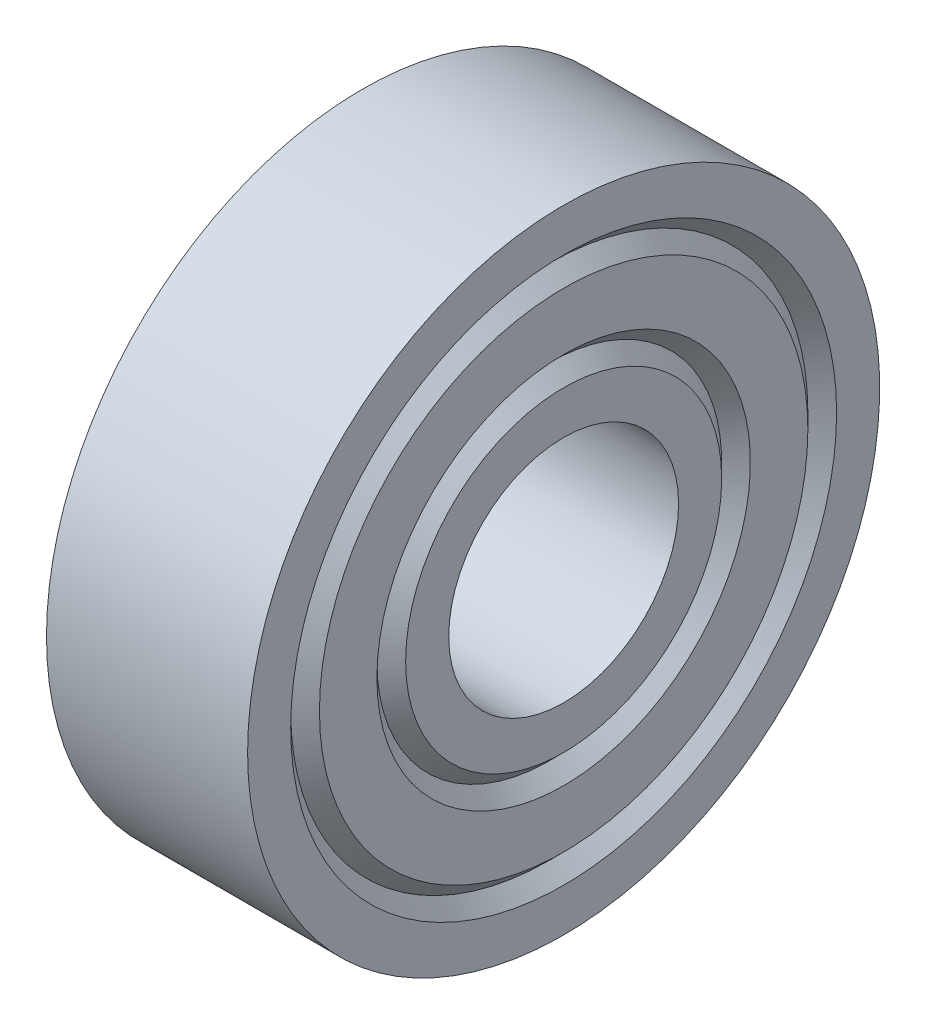
SolidWorks part; units mm, degrees
ref_plane "Face" through (0, 0, 0) normal (0, 0, 1) x (1, 0, 0)
ref_plane "Dessus" through (0, 0, 0) normal (0, 1, 0) x (1, 0, 0)
ref_plane "Droite" through (0, 0, 0) normal (1, 0, 0) x (0, 0, -1)
sketch "Esquisse1" plane through (0, 0, 0) normal (0, 0, 1) x (1, 0, 0)
  line L0 (0, 0) -> (3.5, 0) construction
  line L1 (-3.5, 4) -> (3.5, 4)
  line L2 (3.5, 4) -> (3.5, 5.5)
  line L3 (3.5, 5.5) -> (3, 6)
  line L4 (3, 6) -> (3.5, 6.5)
  line L5 (3.5, 6.5) -> (3.5, 8.5)
  line L6 (3.5, 8.5) -> (3, 9)
  line L7 (3, 9) -> (3.5, 9.5)
  line L8 (3.5, 9.5) -> (3.5, 11)
  line L9 (3.5, 11) -> (-3.5, 11)
  line L10 (-3.5, 11) -> (-3.5, 9.5)
  line L11 (-3.5, 9.5) -> (-3, 9)
  line L12 (-3, 9) -> (-3.5, 8.5)
  line L13 (-3.5, 8.5) -> (-3.5, 6.5)
  line L14 (-3.5, 6.5) -> (-3, 6)
  line L15 (-3, 6) -> (-3.5, 5.5)
  line L16 (-3.5, 5.5) -> (-3.5, 4)
  line L17 (0, 4) -> (0, 0) construction
  dimension "D1" = 7
  dimension "D2" = 4
  dimension "D3" = 11
  dimension "D4" = 1.5
  dimension "D5" = 1.5
  dimension "D6" = 1
  dimension "D7" = 1
  dimension "D8" = 1.5
  dimension "D9" = 1.5
  dimension "D10" = 1
  dimension "D11" = 1
  dimension "D12" = 0.5
  dimension "D13" = 0.5
  dimension "D14" = 0.5
  dimension "D15" = 0.5
  dimension "D16" = 0.5
  dimension "D17" = 0.5
  dimension "D18" = 0.5
  dimension "D19" = 0.5
revolve "Base-Révolution" add sketch "Esquisse1" angle 360 about L0
